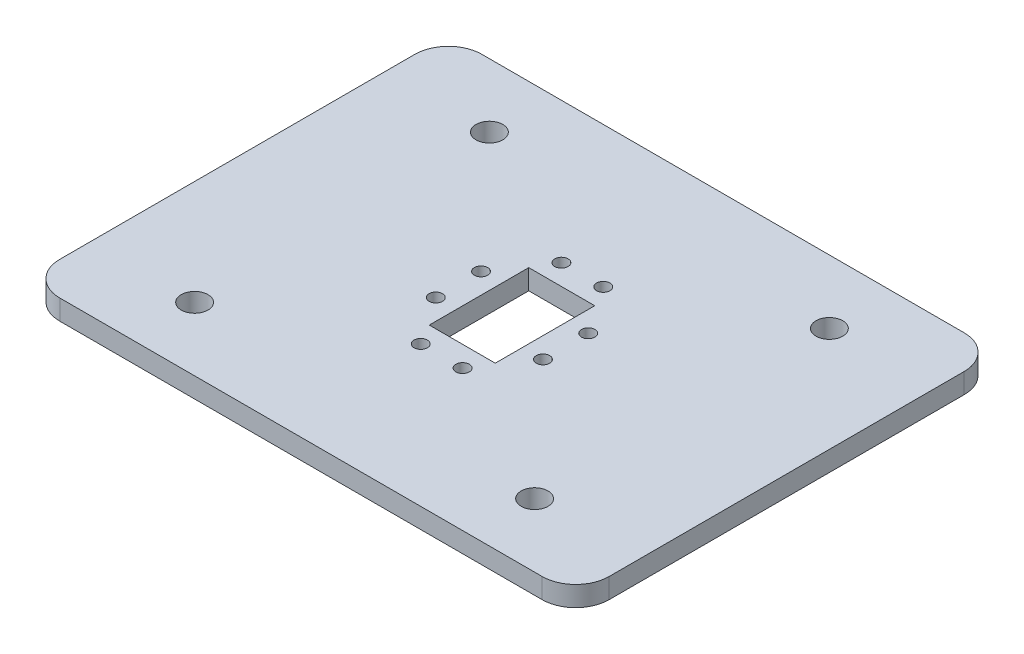
SolidWorks part; units mm, degrees
ref_plane "Front Plane" through (0, 0, 0) normal (0, 0, 1) x (1, 0, 0)
ref_plane "Top Plane" through (0, 0, 0) normal (0, 1, 0) x (1, 0, 0)
ref_plane "Right Plane" through (0, 0, 0) normal (1, 0, 0) x (0, 0, -1)
sketch "Sketch1" plane through (0, 0, 0) normal (0, 1, 0) x (1, 0, 0)
  line L1 (0, 0) -> (-164, 0)
  line L2 (0, 0) -> (0, 126)
  line L3 (0, 126) -> (-164, 126)
  line L4 (-164, 0) -> (-164, 126)
  circle A0 centre (-132.75, 107) radius 4
  circle A1 centre (-31.25, 107) radius 4
  circle A2 centre (-132.75, 19) radius 4
  circle A3 centre (-31.25, 19) radius 4
  point P13 (0, 0)
  point P14 (0, 0)
  point P15 (0, 0)
  point P16 (0, 0)
  dimension "D3" = 8
  dimension "D1" = 164
  dimension "D2" = 126
  dimension "D4" = 31.25
  dimension "D5" = 31.25
  dimension "D6" = 19
  dimension "D7" = 19
extrude "Boss-Extrude1" add sketch "Sketch1" along normal blind 6
fillet "Fillet1" radius 10 4 edges at (-164, 3, -126) (0, 3, -126) (0, 3, 0) (-164, 3, 0)
sketch "Sketch2" plane through (0, 6, 0) normal (0, 1, 0) x (1, 0, 0)
  line L0 (-154, 0) -> (-10, 0) construction
  line L1 (-91.85, 77.85) -> (-72.15, 77.85)
  line L2 (-91.85, 77.85) -> (-91.85, 48.15)
  line L3 (-91.85, 48.15) -> (-72.15, 48.15)
  line L4 (-72.15, 77.85) -> (-72.15, 48.15)
  line L5 (-164, 116) -> (-164, 10) construction
  line L6 (-98, 69.75) -> (-98, 56.25) construction
  line L7 (-88.25, 42) -> (-75.75, 42) construction
  line L8 (-98, 69.75) -> (-91.85, 69.75) construction
  line L9 (-72.15, 69.75) -> (-66, 69.75) construction
  line L10 (-88.25, 84) -> (-88.25, 77.85) construction
  line L11 (-88.25, 42) -> (-88.25, 48.15) construction
  circle A0 centre (-88.25, 84) radius 2
  circle A1 centre (-75.75, 84) radius 2
  circle A2 centre (-98, 69.75) radius 2
  circle A3 centre (-98, 56.25) radius 2
  circle A4 centre (-88.25, 42) radius 2
  circle A5 centre (-75.75, 42) radius 2
  circle A6 centre (-66, 56.25) radius 2
  circle A7 centre (-66, 69.75) radius 2
  point P4 (-82, 48.15)
  point P7 (-82, 0)
  point P8 (-91.85, 63)
  point P11 (-164, 63)
  point P28 (-82, 42)
  point P29 (-98, 63)
  dimension "D3" = 4
  dimension "D1" = 29.7
  dimension "D2" = 19.7
  dimension "D4" = 12.5
  dimension "D5" = 13.5
  dimension "D6" = 32
  dimension "D7" = 42
extrude "Cut-Extrude1" cut sketch "Sketch2" against normal through all
